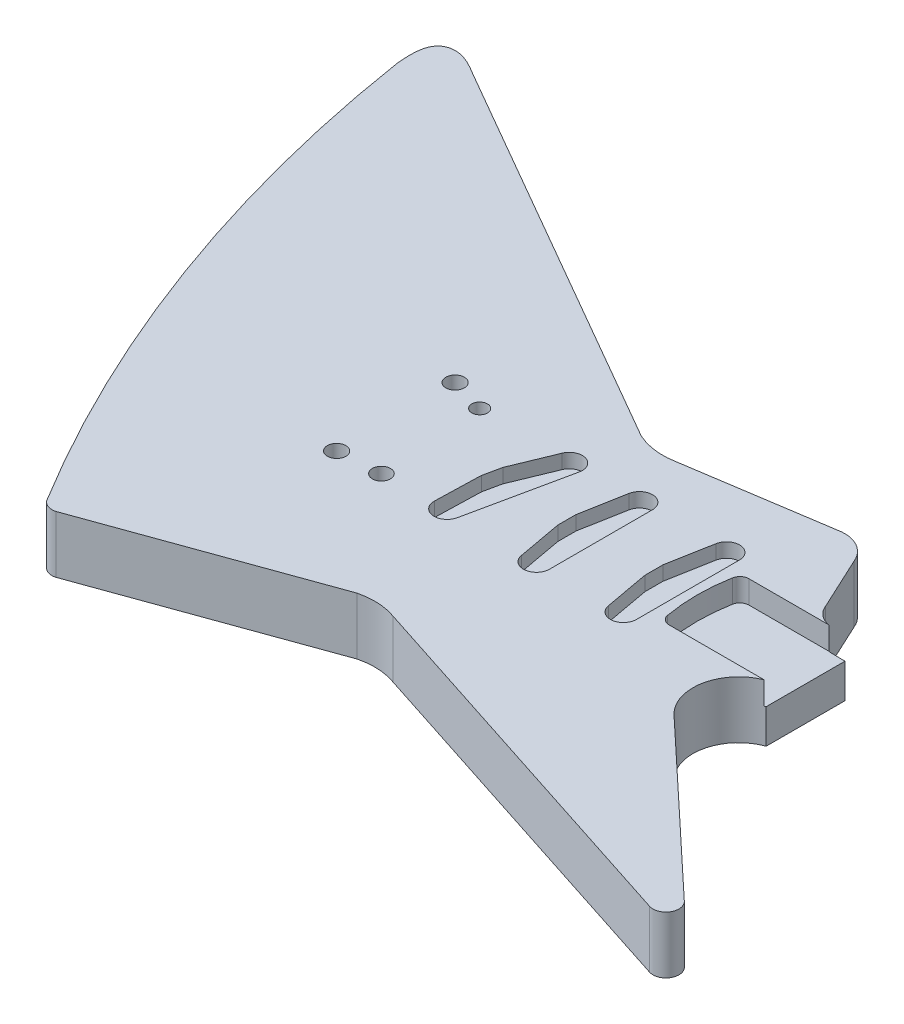
SolidWorks part; units mm, degrees
ref_plane "Front Plane" through (0, 0, 0) normal (0, 0, 1) x (1, 0, 0)
ref_plane "Top Plane" through (0, 0, 0) normal (0, 1, 0) x (1, 0, 0)
ref_plane "Right Plane" through (0, 0, 0) normal (1, 0, 0) x (0, 0, -1)
ref_plane "Plane1" through (0, 20, 0) normal (0, 1, 0) x (1, 0, 0)
sketch "Sketch1" plane through (0, 20, 0) normal (0, 1, 0) x (1, 0, 0)
  line L0 (563.9649, 507.5137) -> (563.9649, 562.7364)
  line L1 (563.9649, 562.7364) -> (554.6908, 562.8948)
  line L2 (539.8539, 573.2061) -> (522.5243, 610.43)
  line L3 (497.9312, 623.6342) -> (399.8309, 608.6087)
  line L4 (371.9236, 612.0224) -> (95.3107, 771.4941)
  line L5 (212.6322, 361.1733) -> (367.6546, 417.0844)
  line L6 (394.091, 415.822) -> (660.2315, 329.5749)
  line L7 (669.267, 344.8773) -> (553.7312, 453.2399)
  arc A0 (554.6908, 562.8948) -> (539.8539, 573.2061) centre (554.9679, 579.1236) cw
  arc A1 (522.5243, 610.43) -> (497.9312, 623.6342) centre (502.4406, 602.5283) ccw
  arc A2 (399.8309, 608.6087) -> (371.9236, 612.0224) centre (391.2113, 653.9219) cw
  arc A3 (60.287, 752.9025) -> (202.7629, 364.7399) centre (1107.1005, 916.9084) ccw
  arc A4 (202.7629, 364.7399) -> (212.6322, 361.1733) centre (210.2265, 369.9546) ccw
  arc A5 (367.6546, 417.0844) -> (394.091, 415.822) centre (378.7977, 372.9989) cw
  arc A6 (660.2315, 329.5749) -> (669.267, 344.8773) centre (663.0383, 338.2363) ccw
  arc A7 (553.7312, 453.2399) -> (563.9649, 507.5137) centre (574.8412, 477.3612) cw
  spline S0 degree 3 poles (60.287, 752.9025) (59.4087, 762.7695) (58.561, 776.2044) (76.9429, 783.2985) (86.7531, 776.4937) (95.3107, 771.4941) knots 0 0 0 0 0.5 0.5 1 1 1 1
extrude "Boss-Extrude1" add sketch "Sketch1" against normal blind 40
ref_plane "Plane2" through (0, 0, -514.7664) normal (0, 0, 1) x (1, 0, 0)
hole_wizard "Ø13.0 (13) Diameter Hole1" positions "Sketch12" profile "Sketch11" hole size "Ø13.0" standard "ANSI Metric"
sketch "Sketch12" plane through (0, 20, 0) normal (0, 1, 0) x (1, 0, 0)
  point P0 (274.3359, 496.2335)
  point P1 (274.3359, 579.2131)
sketch "Sketch11" plane through (274.3359, 20, -496.2335) normal (1, 0, 0) x (0, 0, 1)
  line L0 (0, 0) -> (0, 29)
  line L1 (0, 29) -> (6.5, 29)
  line L2 (6.5, 29) -> (6.5, 0)
  line L5 (6.5, 0) -> (0, 0)
  line L10 (0, 29) -> (-6.5, 29) construction
  line L11 (0, -6.35) -> (0, 107.95) construction
  dimension "Hole Dia." = 13
  dimension "Hole Depth" = 29
  dimension "Drill Angle" = 180
sketch "Sketch13" plane through (0, 20, 0) normal (0, 1, 0) x (1, 0, 0)
  line L5 (563.9649, 535.1251) -> (484.3582, 535.1251) construction
  line L6 (563.9649, 563.1251) -> (496.2732, 563.1251)
  line L7 (563.9649, 563.1251) -> (563.9649, 507.1251)
  line L8 (563.9649, 507.1251) -> (496.2732, 507.1251)
  line L9 (491.0899, 563.1251) -> (491.0899, 507.1251) construction
  line L10 (563.9649, 563.1251) -> (491.0899, 507.1251) construction
  line L11 (563.9649, 507.1251) -> (491.0899, 563.1251) construction
  line L12 (563.9649, 507.5137) -> (563.9649, 562.7364) construction
  arc A0 (490.0263, 512.3356) -> (490.0263, 557.9145) centre (614.9649, 535.1251) cw
  arc A1 (490.0263, 557.9145) -> (496.2732, 563.1251) centre (496.2732, 556.7751) cw
  arc A2 (496.2732, 507.1251) -> (490.0263, 512.3356) centre (496.2732, 513.4751) cw
  point P2 (527.5274, 535.1251)
  point P4 (487.9649, 535.1251)
  dimension "D4" = 6.35
  dimension "D1" = 56
  dimension "D2" = 127
  dimension "D3" = 76
extrude "Cut-Extrude8" cut sketch "Sketch13" against normal blind 16
sketch "Sketch14" plane through (0, 20, 0) normal (0, 1, 0) x (1, 0, 0)
  line L0 (303.8149, 498.1314) -> (303.8149, 572.1187) construction
  line L1 (303.8149, 498.1314) -> (298.6412, 572.1187) construction
  line L2 (487.9649, 535.1251) -> (303.8149, 535.1251) construction
  line L3 (298.6412, 572.1187) -> (303.8149, 572.1187) construction
  circle A0 centre (303.8149, 498.1314) radius 6.35
  circle A1 centre (298.6412, 572.1187) radius 5.5026
  arc A2 (490.0263, 557.9145) -> (490.0263, 512.3356) centre (614.9649, 535.1251) ccw construction
  arc A3 (490.0263, 557.9145) -> (490.0263, 512.3356) centre (614.9649, 535.1251) ccw construction
  point P8 (487.9649, 535.1251)
  dimension "D2" = 12.7
  dimension "D1" = 184.15
  dimension "D3" = 4
  dimension "D4" = 74.168
extrude "Cut-Extrude9" cut sketch "Sketch14" against normal blind 10
sketch "Sketch17" plane through (0, 20, 0) normal (0, 1, 0) x (1, 0, 0)
  line L0 (487.9649, 535.1251) -> (-189.813, 535.1251) construction
  line L1 (472.4709, 571.208) -> (472.4709, 499.0422) construction
  line L2 (481.6149, 571.208) -> (481.6149, 499.0422) construction
  line L3 (463.3269, 571.208) -> (463.3269, 499.0422) construction
  line L4 (481.6149, 499.0422) -> (481.6149, 571.208)
  line L5 (463.476, 572.8526) -> (457.7389, 541.4751)
  line L6 (457.7389, 541.4751) -> (457.7389, 528.7751)
  line L7 (457.7389, 528.7751) -> (463.476, 497.3975)
  line L8 (420.6549, 499.0422) -> (420.6549, 571.208)
  line L9 (402.516, 572.8526) -> (396.7789, 541.4751)
  line L10 (396.7789, 541.4751) -> (396.7789, 528.7751)
  line L11 (396.7789, 528.7751) -> (402.516, 497.3975)
  line L12 (411.5109, 571.208) -> (411.5109, 499.0422) construction
  line L13 (357.073, 497.9295) -> (372.0771, 568.5183)
  line L14 (354.6765, 573.8983) -> (342.541, 544.3993)
  line L15 (342.541, 544.3993) -> (339.9005, 531.9768)
  line L16 (339.9005, 531.9768) -> (338.9885, 500.0921)
  line L17 (355.6309, 571.208) -> (355.6309, 499.0422) construction
  line L18 (363.1329, 570.4195) -> (348.1288, 499.8307) construction
  arc A0 (490.0263, 557.9145) -> (490.0263, 512.3356) centre (614.9649, 535.1251) ccw construction
  arc A1 (481.6149, 571.208) -> (463.3269, 571.208) centre (472.4709, 571.208) ccw construction
  arc A2 (463.3269, 499.0422) -> (481.6149, 499.0422) centre (472.4709, 499.0422) ccw construction
  arc A3 (481.6149, 571.208) -> (463.476, 572.8526) centre (472.4709, 571.208) ccw
  arc A4 (481.6149, 499.0422) -> (463.476, 497.3975) centre (472.4709, 499.0422) cw
  arc A5 (420.6549, 571.208) -> (402.516, 572.8526) centre (411.5109, 571.208) ccw
  arc A6 (420.6549, 499.0422) -> (402.516, 497.3975) centre (411.5109, 499.0422) cw
  arc A7 (372.0771, 568.5183) -> (354.6765, 573.8983) centre (363.1329, 570.4195) ccw
  arc A8 (357.073, 497.9295) -> (338.9885, 500.0921) centre (348.1288, 499.8307) cw
  point P8 (472.4709, 535.1251)
  point P16 (457.7389, 535.1251)
  point P42 (355.6309, 535.1251)
  dimension "D1" = 6.35
  dimension "D2" = 18.288
  dimension "D3" = 12.7
  dimension "D4" = 23.876
  dimension "D6" = 60.96
  dimension "D7" = 12
  dimension "D8" = 55.88
  dimension "D5" = 2
extrude "Cut-Extrude10" cut sketch "Sketch17" against normal blind 10
